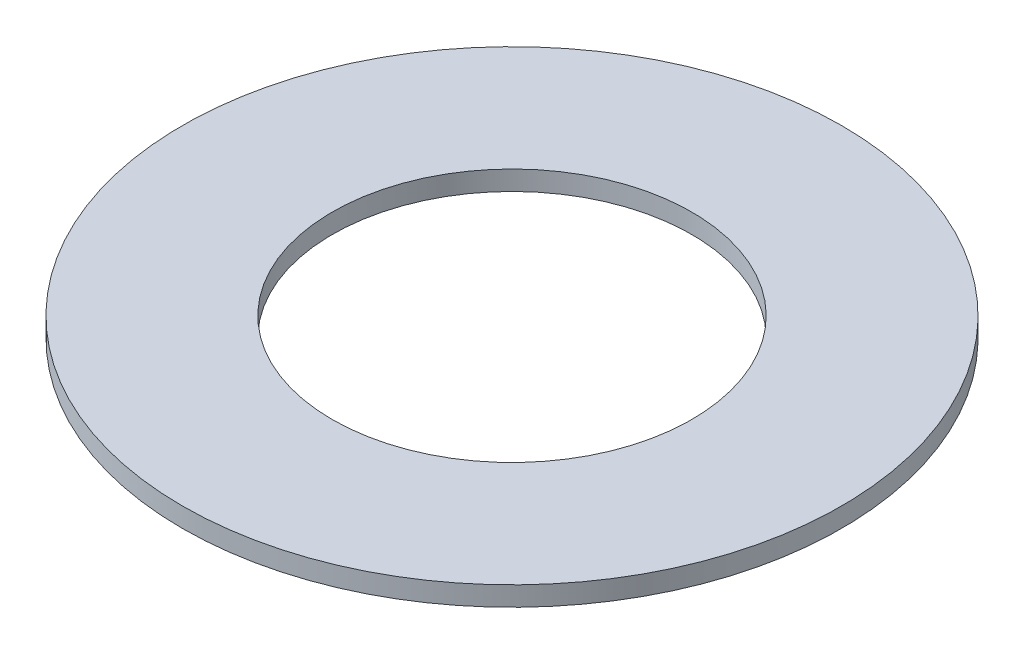
SolidWorks part; units mm, degrees
ref_plane "Alzado" through (0, 0, 0) normal (0, 0, 1) x (1, 0, 0)
ref_plane "Planta" through (0, 0, 0) normal (0, 1, 0) x (1, 0, 0)
ref_plane "Vista lateral" through (0, 0, 0) normal (1, 0, 0) x (0, 0, -1)
sketch "Croquis1" plane through (0, 0, 0) normal (0, 1, 0) x (1, 0, 0)
  circle A0 centre (0, 0) radius 6
  circle A1 centre (0, 0) radius 11
  dimension "D1" = 22
  dimension "D2" = 12
extrude "Saliente-Extruir1" add sketch "Croquis1" along normal blind 0.65
